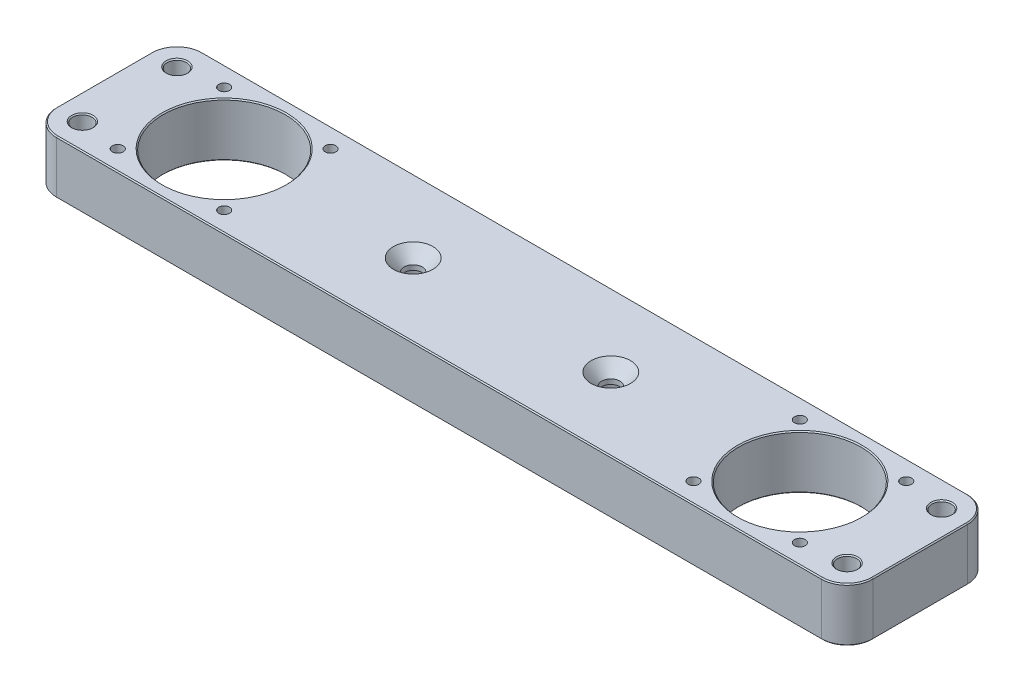
SolidWorks part; units mm, degrees
material "6061-T6 Aluminum"
ref_plane "Front Plane" through (0, 0, 0) normal (0, 0, 1) x (1, 0, 0)
ref_plane "Top Plane" through (0, 0, 0) normal (0, 1, 0) x (1, 0, 0)
ref_plane "Right Plane" through (0, 0, 0) normal (1, 0, 0) x (0, 0, -1)
sketch "Sketch1" plane through (0, 0, 0) normal (0, 1, 0) x (1, 0, 0)
  line L1 (-190, -34) -> (190, -34)
  line L2 (-190, -34) -> (-190, 34)
  line L3 (-190, 34) -> (190, 34)
  line L4 (190, -34) -> (190, 34)
  line L5 (-190, -34) -> (190, 34) construction
  line L6 (-190, 34) -> (190, -34) construction
  point P0 (0, 0)
  dimension "D1" = 68
  dimension "D2" = 380
extrude "Boss-Extrude1" add sketch "Sketch1" along normal blind 25
sketch "Sketch2" plane through (0, 25, 0) normal (0, 1, 0) x (1, 0, 0)
  line L0 (-134, 0) -> (0, 0) construction
  line L1 (0, 0) -> (134, 0) construction
  circle A0 centre (-134, 0) radius 28.5
  circle A1 centre (134, 0) radius 28.5
  dimension "D1" = 268
  dimension "D2" = 57
extrude "Cut-Extrude1" cut sketch "Sketch2" against normal through all
sketch "Sketch3" [suppressed] plane through (0, 0, 0) normal (0, -1, 0) x (1, 0, 0)
  line L1 (36, 0) -> (0, 0) construction
  line L2 (0, 0) -> (-36, 0) construction
  circle A1 centre (-36, 0) radius 14.2875
  circle A3 centre (36, 0) radius 14.2875
  circle A4 centre (94, 0) radius 22.987 construction
  circle A5 centre (94, 0) radius 22.987
  circle A6 centre (-94, 0) radius 22.987 construction
  circle A7 centre (-94, 0) radius 22.987
  dimension "D2" = 28.575
  dimension "D1" = 72
sketch "Sketch4" plane through (0, 25, 0) normal (0, 1, 0) x (1, 0, 0)
  line L0 (46, 0) -> (0, 0) construction
  line L1 (0, 0) -> (-46, 0) construction
  circle A0 centre (-46, 0) radius 9.55
  circle A1 centre (46, 0) radius 9.55
  dimension "D1" = 19.1
  dimension "D2" = 92
extrude "Cut-Extrude2" cut sketch "Sketch4" against normal through all both and the other way through all
chamfer "Chamfer1" distance 0.5 angle 45 8 edges at (134, 25, 28.5) (134, 0, 28.5) (46, 25, -9.55) (46, 0, 9.55) (-46, 25, -9.55) (-46, 0, 9.55) (-134, 25, 28.5) (-134, 0, 28.5)
fillet "Fillet1" radius 12 4 edges at (190, 12.5, 34) (190, 12.5, -34) (-190, 12.5, -34) (-190, 12.5, 34)
hole_wizard "M8 Clearance Hole1" positions "Sketch5" profile "Sketch6" hole size "M8" standard "ANSI Metric" end condition through all
sketch "Sketch5" plane through (0, 0, 0) normal (0, 1, 0) x (1, 0, 0)
  point P0 (-178, 22)
  point P3 (-178, -22)
  point P6 (178, 22)
  point P9 (178, -22)
sketch "Sketch6" plane through (-178, 0, -22) normal (1, 0, 0) x (0, 0, -1)
  line L0 (0, 0) -> (0, 25)
  line L1 (0, 25) -> (4.5, 25)
  line L2 (4.5, 25) -> (4.5, 0)
  line L5 (4.5, 0) -> (0, 0)
  line L11 (0, -6.35) -> (0, 107.95) construction
  dimension "Thru Hole Dia." = 9
  dimension "Thru Hole Depth" = 25
chamfer "Chamfer2" distance 0.5 angle 45 8 edges at (0, 0, -34) (-186.4853, 0, -30.4853) (186.4853, 0, -30.4853) (-190, 0, 0) (190, 0, 0) (-186.4853, 0, 30.4853) (186.4853, 0, 30.4853) (0, 0, 34)
chamfer "Chamfer3" distance 0.5 angle 45 16 edges at (178, 25, 17.5) (178, 25, -26.5) (-178, 25, 17.5) (-178, 25, -26.5) (178, 0, -26.5) (178, 0, 17.5) (-178, 0, 17.5) (-178, 0, -26.5) (186.4853, 25, 30.4853) (190, 25, 0) (0, 25, 34) (186.4853, 25, -30.4853) (-186.4853, 25, 30.4853) (0, 25, -34) (-190, 25, 0) (-186.4853, 25, -30.4853)
sketch "Sketch7" plane through (0, 0, 0) normal (0, -1, 0) x (1, 0, 0)
  line L1 (109.235, 24.765) -> (158.765, 24.765) construction
  line L2 (109.235, 24.765) -> (109.235, -24.765) construction
  line L3 (109.235, -24.765) -> (158.765, -24.765) construction
  line L4 (158.765, 24.765) -> (158.765, -24.765) construction
  line L5 (109.235, 24.765) -> (158.765, -24.765) construction
  line L6 (109.235, -24.765) -> (158.765, 24.765) construction
  line L7 (-158.765, 24.765) -> (-109.235, 24.765) construction
  line L8 (-158.765, 24.765) -> (-158.765, -24.765) construction
  line L9 (-158.765, -24.765) -> (-109.235, -24.765) construction
  line L10 (-109.235, 24.765) -> (-109.235, -24.765) construction
  line L11 (-158.765, 24.765) -> (-109.235, -24.765) construction
  line L12 (-158.765, -24.765) -> (-109.235, 24.765) construction
  circle A0 centre (109.235, 24.765) radius 3.302 construction
  circle A1 centre (158.765, -24.765) radius 3.302 construction
  circle A2 centre (158.765, 24.765) radius 3.302 construction
  circle A3 centre (109.235, -24.765) radius 3.302 construction
  circle A4 centre (109.235, 24.765) radius 3.302
  circle A5 centre (158.765, -24.765) radius 3.302
  circle A6 centre (158.765, 24.765) radius 3.302
  circle A7 centre (109.235, -24.765) radius 3.302
  circle A12 centre (-158.765, -24.765) radius 3.302
  circle A13 centre (-109.235, -24.765) radius 3.302
  circle A14 centre (-109.235, 24.765) radius 3.302
  circle A15 centre (-158.765, 24.765) radius 3.302
  point P13 (134, 0)
  point P15 (-134, 0)
hole_wizard "M6x1.0 Tapped Hole1" positions "Sketch8" profile "Sketch9" tap size "M6x1.0" standard "ANSI Metric" end condition through all
sketch "Sketch8" plane through (0, 0, 0) normal (0, -1, 0) x (-1, 0, 0)
  point P0 (158.765, -24.765)
  point P3 (109.235, -24.765)
  point P6 (109.235, 24.765)
  point P9 (158.765, 24.765)
  point P12 (-109.235, -24.765)
  point P15 (-158.765, -24.765)
  point P18 (-109.235, 24.765)
  point P21 (-158.765, 24.765)
cosmetic thread "Hole Thread1" parameters "D2"=6
cosmetic thread "Hole Thread10" parameters "D2"=6
cosmetic thread "Hole Thread11" parameters "D2"=6
cosmetic thread "Hole Thread12" parameters "D2"=6
cosmetic thread "Hole Thread13" parameters "D2"=6
cosmetic thread "Hole Thread14" parameters "D2"=6
cosmetic thread "Hole Thread16" parameters "D2"=6
sketch "Sketch9" plane through (-158.765, 0, 24.765) normal (1, 0, 0) x (0, 0, -1)
  line L0 (0, 0) -> (0, 25)
  line L1 (0, 25) -> (2.5, 25)
  line L2 (2.5, 25) -> (2.5, 0)
  line L5 (2.5, 0) -> (0, 0)
  line L11 (0, -6.35) -> (0, 107.95) construction
  dimension "Thru Tap Drill Dia." = 5
  dimension "Thru Tap Drill Depth" = 25
cosmetic thread "Hole Thread17" parameters "D2"=6
sketch "Sketch10" plane through (0, 0, 0) normal (0, -1, 0) x (1, 0, 0)
  line L1 (169, 55.9508) -> (99, 55.9508)
  line L2 (169, 55.9508) -> (169, -55.9508)
  line L3 (169, -55.9508) -> (99, -55.9508)
  line L4 (99, 55.9508) -> (99, -55.9508)
  line L5 (169, 55.9508) -> (99, -55.9508) construction
  line L6 (169, -55.9508) -> (99, 55.9508) construction
  point P0 (134, 0)
  dimension "D1" = 70
extrude "Cut-Extrude3" [suppressed] cut sketch "Sketch10" against normal blind 6
mirror "Mirror1" [suppressed] about plane through (0, 0, 0) normal (1, 0, 0)
sketch "Sketch11" plane through (0, 0, 0) normal (0, -1, 0) x (1, 0, 0)
  line L1 (37.5, 15) -> (-37.5, 15)
  line L2 (37.5, 15) -> (37.5, 43.9732)
  line L3 (37.5, 43.9732) -> (-37.5, 43.9732)
  line L4 (-37.5, 15) -> (-37.5, 43.9732)
  line L6 (0, 0) -> (0, 15) construction
  dimension "D1" = 15
  dimension "D2" = 75
extrude "Cut-Extrude4" [suppressed] cut sketch "Sketch11" against normal blind 8
mirror "Mirror2" [suppressed] about plane through (0, 0, 0) normal (0, 0, 1)
fillet "Fillet2" [suppressed] radius 10
fillet "Fillet3" [suppressed] radius 4
chamfer "Chamfer4" [suppressed] distance 0.5 angle 45
sketch "Sketch12" plane through (0, 25, 0) normal (0, 1, 0) x (1, 0, 0)
  circle A0 centre (46, 0) radius 10.05
  circle A1 centre (-46, 0) radius 10.05
  circle A2 centre (46, 0) radius 10.05 construction
  circle A3 centre (-46, 0) radius 10.05 construction
  circle A4 centre (46, 0) radius 4.5
  circle A5 centre (-46, 0) radius 4.5
  dimension "D1" = 9
extrude "Boss-Extrude2" [suppressed] add sketch "Sketch12" against normal blind 4
fillet "Fillet4" [suppressed] radius 3
chamfer "Chamfer5" [suppressed] distance 1 angle 45
sketch "Sketch13" plane through (0, 25, 0) normal (0, 1, 0) x (1, 0, 0)
  circle A0 centre (46, 0) radius 13.411
  circle A1 centre (-46, 0) radius 14.7245
extrude "Boss-Extrude3" add sketch "Sketch13" against normal blind 8
hole_wizard "CSK for 5/16 Flat Head Socket Cap Screw1" positions "Sketch14" profile "Sketch15" countersink size "5/16" standard "ANSI Inch" end condition through all
sketch "Sketch14" plane through (0, 25, 0) normal (0, 1, 0) x (1, 0, 0)
  point P0 (46, 0)
  point P3 (-46, 0)
sketch "Sketch15" plane through (46, 25, 0) normal (1, 0, 0) x (0, 0, 1)
  line L0 (0, 0) -> (0, 25)
  line L1 (0, 25) -> (4.2164, 25)
  line L2 (4.2164, 25) -> (4.2164, 5.7335)
  line L3 (4.2164, 5.7335) -> (9.2005, 0)
  line L5 (9.2005, 0) -> (0, 0)
  line L6 (-4.2164, 5.7335) -> (-9.2005, 0) construction
  line L11 (0, -6.35) -> (0, 107.95) construction
  dimension "Thru Hole Dia." = 8.4328
  dimension "Thru Hole Depth" = 25
  dimension "Near C'Sink Dia." = 18.401
  dimension "Near C'Sink Angle" = 82
chamfer "Chamfer6" [suppressed] distance 0.5 angle 45
